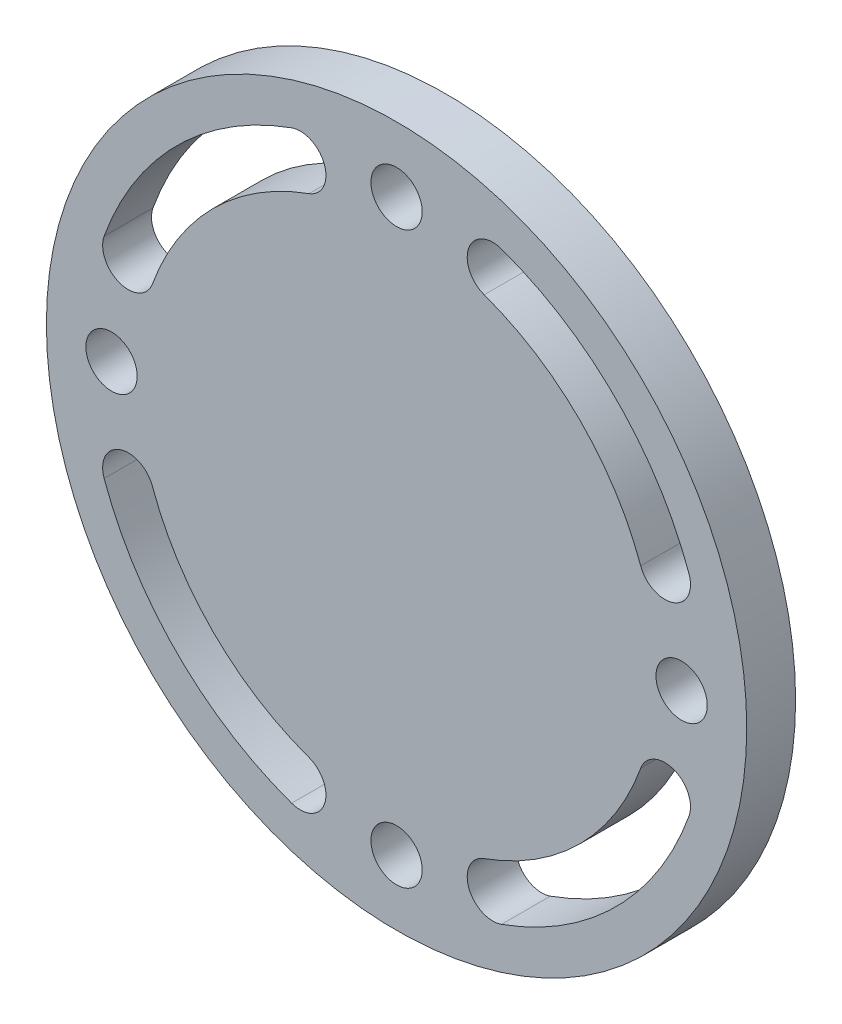
SolidWorks part; units mm, degrees
material "Thornel Mat VMA"
ref_plane "前视基准面" through (0, 0, 0) normal (0, 0, 1) x (1, 0, 0)
ref_plane "上视基准面" through (0, 0, 0) normal (0, 1, 0) x (1, 0, 0)
ref_plane "右视基准面" through (0, 0, 0) normal (1, 0, 0) x (0, 0, -1)
sketch "草图1" plane through (0, 0, 0) normal (0, 0, 1) x (1, 0, 0)
  line L0 (0, 0) -> (-50000, 0) construction
  line L1 (0, 0) -> (0, 50000) construction
  circle A1 centre (0, 0) radius 17.5 construction
  circle A2 centre (0, 0) radius 21.5
  circle A3 centre (0, 17.5) radius 1.575
  circle A4 centre (17.5, 0) radius 1.575
  circle A5 centre (0, -17.5) radius 1.575
  circle A6 centre (-17.5, 0) radius 1.575
  arc A9 (-5.3792, 14.989) -> (-6.4432, 17.9539) centre (-5.9112, 16.4714) ccw
  arc A10 (-17.9539, 6.4432) -> (-14.989, 5.3792) centre (-16.4714, 5.9112) ccw
  arc A11 (-6.4432, 17.9539) -> (-17.9539, 6.4432) centre (0, 0) ccw
  arc A12 (-5.3792, 14.989) -> (-14.989, 5.3792) centre (0, 0) ccw
  arc A13 (5.3792, 14.989) -> (14.989, 5.3792) centre (0, 0) cw
  arc A14 (6.4432, 17.9539) -> (17.9539, 6.4432) centre (0, 0) cw
  arc A15 (17.9539, 6.4432) -> (14.989, 5.3792) centre (16.4714, 5.9112) cw
  arc A16 (5.3792, 14.989) -> (6.4432, 17.9539) centre (5.9112, 16.4714) cw
  arc A17 (5.3792, -14.989) -> (6.4432, -17.9539) centre (5.9112, -16.4714) ccw
  arc A18 (17.9539, -6.4432) -> (14.989, -5.3792) centre (16.4714, -5.9112) ccw
  arc A19 (6.4432, -17.9539) -> (17.9539, -6.4432) centre (0, 0) ccw
  arc A20 (5.3792, -14.989) -> (14.989, -5.3792) centre (0, 0) ccw
  arc A21 (-5.3792, -14.989) -> (-14.989, -5.3792) centre (0, 0) cw
  arc A22 (-6.4432, -17.9539) -> (-17.9539, -6.4432) centre (0, 0) cw
  arc A23 (-17.9539, -6.4432) -> (-14.989, -5.3792) centre (-16.4714, -5.9112) cw
  arc A24 (-5.3792, -14.989) -> (-6.4432, -17.9539) centre (-5.9112, -16.4714) cw
  point P16 (0, 0)
  dimension "D2" = 35
  dimension "D3" = 4
  dimension "D4" = 3.15
  dimension "D8" = 1.575
  dimension "D9" = 19.075
  dimension "D10" = 15.925
  dimension "D11" = 1.575
  dimension "D6" = 6
  dimension "D7" = 6
  dimension "D5" = 4
extrude "凸台-拉伸1" add sketch "草图1" along normal blind 3
